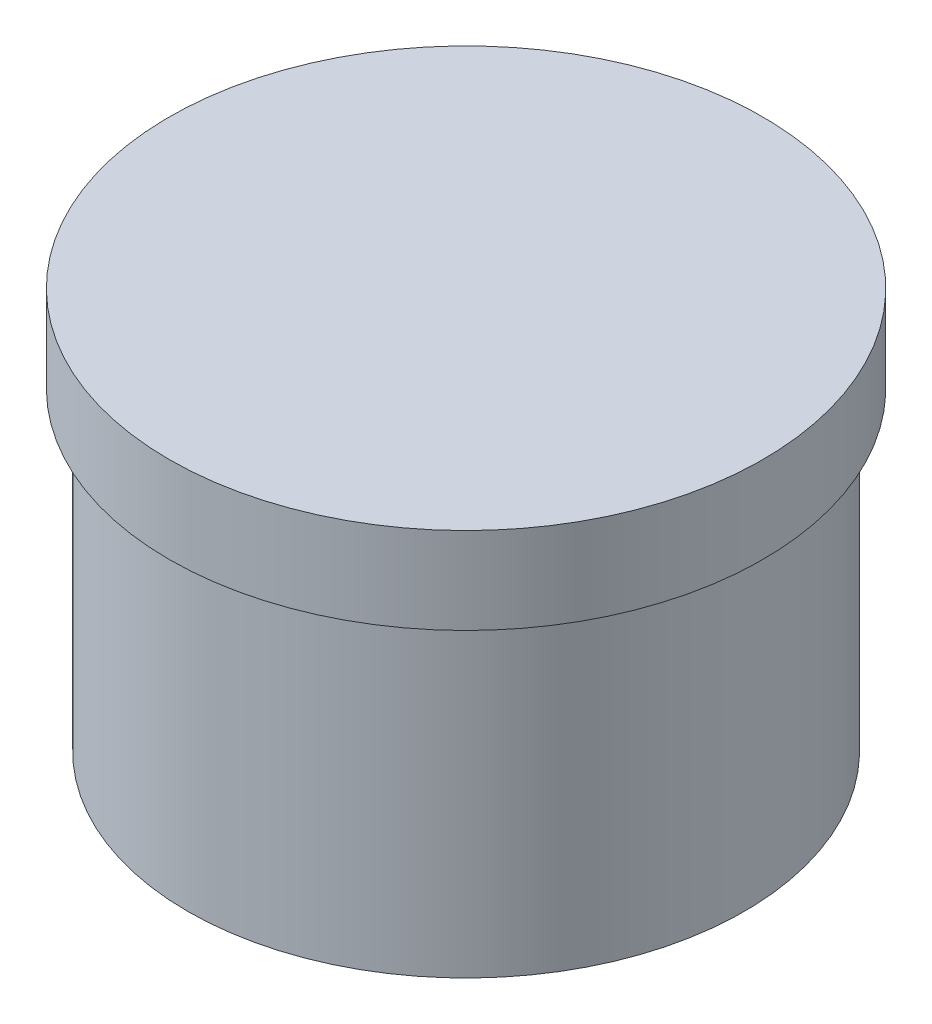
SolidWorks part; units mm, degrees
ref_plane "Front Plane" through (0, 0, 0) normal (0, 0, 1) x (1, 0, 0)
ref_plane "Top Plane" through (0, 0, 0) normal (0, 1, 0) x (1, 0, 0)
ref_plane "Right Plane" through (0, 0, 0) normal (1, 0, 0) x (0, 0, -1)
sketch "Sketch1" plane through (0, 0, 0) normal (0, 1, 0) x (1, 0, 0)
  circle A0 centre (0, 0) radius 22.5
  dimension "D1" = 45
extrude "Boss-Extrude1" add sketch "Sketch1" against normal blind 25.4
sketch "Sketch2" plane through (0, 0, 0) normal (0, 1, 0) x (1, 0, 0)
  circle A0 centre (0, 0) radius 24
  dimension "D1" = 48
extrude "Boss-Extrude2" add sketch "Sketch2" along normal blind 7
sketch "Sketch3" plane through (0, 7, 0) normal (0, 1, 0) x (1, 0, 0)
  circle A0 centre (0, 24) radius 1
  circle A1 centre (0, 0) radius 24 construction
  dimension "D1" = 2
